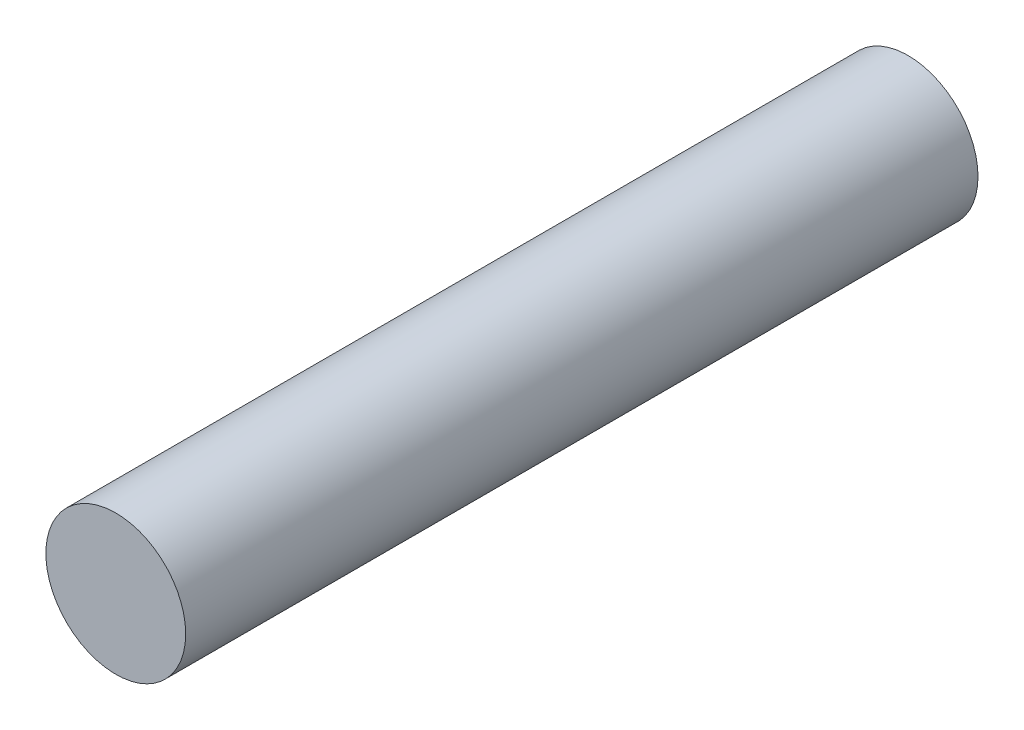
SolidWorks part; units mm, degrees
material "201 Annealed Stainless Steel (SS)"
ref_plane "Front Plane" through (0, 0, 0) normal (0, 0, 1) x (1, 0, 0)
ref_plane "Top Plane" through (0, 0, 0) normal (0, 1, 0) x (1, 0, 0)
ref_plane "Right Plane" through (0, 0, 0) normal (1, 0, 0) x (0, 0, -1)
sketch "Sketch1" plane through (0, 0, 0) normal (0, 0, 1) x (1, 0, 0)
  circle A0 centre (0, 0) radius 3
  dimension "D1" = 6
extrude "Boss-Extrude1" add sketch "Sketch1" along normal mid plane 34 contours A0
cosmetic thread "Cosmetic Thread1"
cosmetic thread "Cosmetic Thread2"
